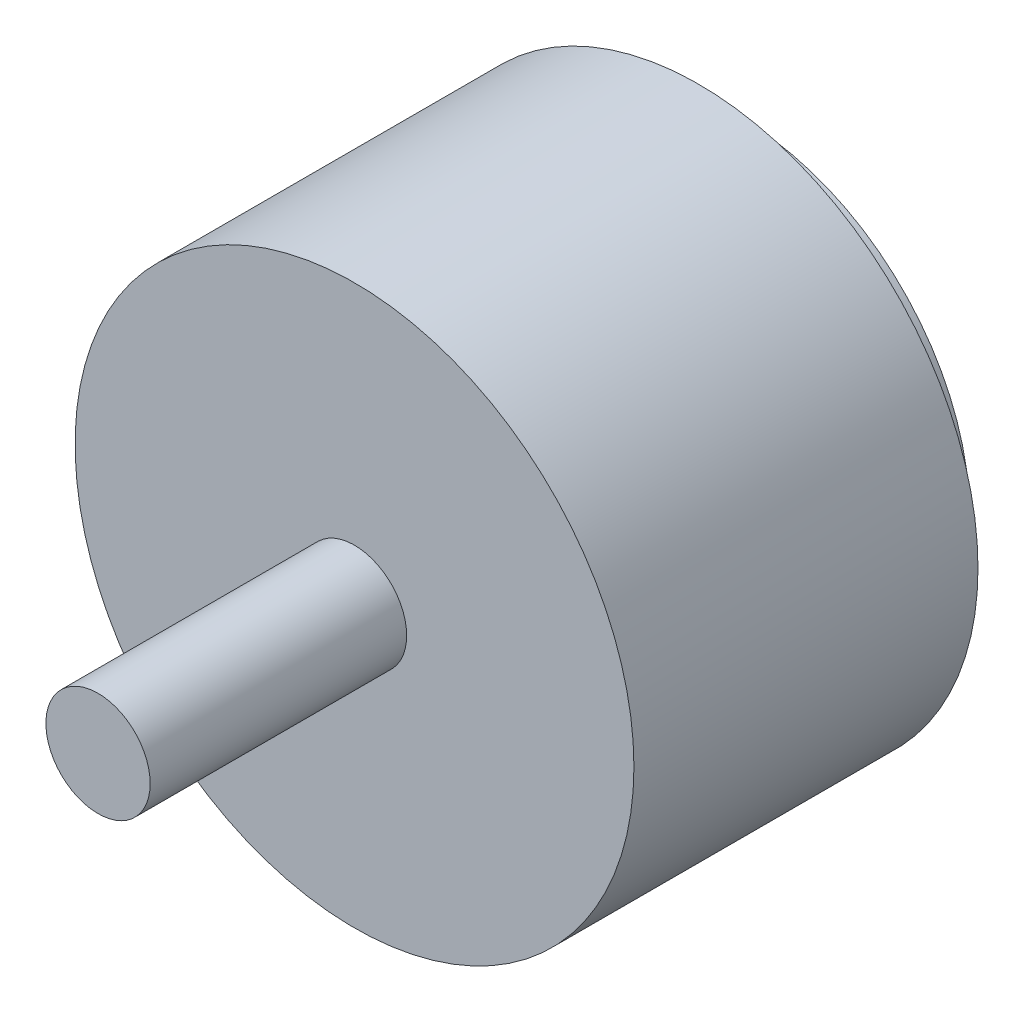
SolidWorks part; units mm, degrees
ref_plane "前视基准面" through (0, 0, 0) normal (0, 0, 1) x (1, 0, 0)
ref_plane "上视基准面" through (0, 0, 0) normal (0, 1, 0) x (1, 0, 0)
ref_plane "右视基准面" through (0, 0, 0) normal (1, 0, 0) x (0, 0, -1)
other "Configuration Table"
sketch "草图1" plane through (0, 0, 0) normal (0, 0, 1) x (1, 0, 0)
  circle A0 centre (0, 0) radius 13.4
  circle A1 centre (0, 0) radius 4.5
extrude "钟罩及定子总包络_D26p8H18p5" add sketch "草图1" along normal blind 16.5
sketch "草图2" plane through (0, 0, 0) normal (0, 0, 1) x (1, 0, 0)
  circle A0 centre (0, 0) radius 13.4
extrude "钟罩顶盖闭合" add sketch "草图2" along normal blind 1.5 from offset 15
sketch "草图3" plane through (0, 0, 0) normal (0, 0, 1) x (1, 0, 0)
  circle A2 centre (0, 0) radius 11
extrude "电机底座" add sketch "草图3" along normal blind 2 from offset 2
sketch "草图4" plane through (0, 0, 0) normal (0, 0, 1) x (1, 0, 0)
  circle A0 centre (0, 0) radius 2.5
extrude "M5桨轴包络" add sketch "草图4" along normal blind 12.3 from offset 16.5
sketch "草图5" plane through (0, 0, 0) normal (0, 0, 1) x (1, 0, 0)
  circle A0 centre (-8, 0) radius 1.6
  circle A1 centre (0, -8) radius 1.6
  circle A2 centre (8, 0) radius 1.6
  circle A3 centre (0, 8) radius 1.6
extrude "D16分度圆四M3简化安装孔" cut sketch "草图5" along normal blind 5 from offset 2
